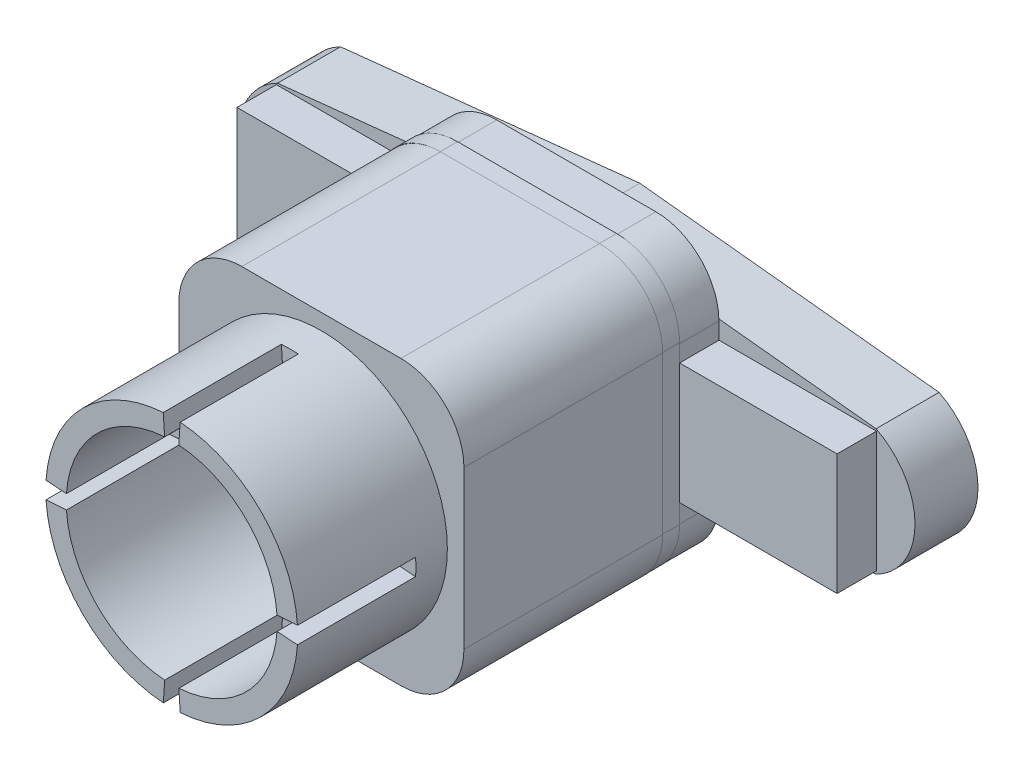
SolidWorks part; units mm, degrees
ref_plane "Front Plane" through (0, 0, 0) normal (0, 0, 1) x (1, 0, 0)
ref_plane "Top Plane" through (0, 0, 0) normal (0, 1, 0) x (1, 0, 0)
ref_plane "Right Plane" through (0, 0, 0) normal (1, 0, 0) x (0, 0, -1)
sketch "Sketch1" plane through (0, 0, 0) normal (0, 0, 1) x (1, 0, 0)
  line L12 (-5.05, 9.0001) -> (5.05, 9.0001)
  line L13 (-9.05, 5.0001) -> (-9.05, -5.0001)
  line L14 (-5.05, -9.0001) -> (5.05, -9.0001)
  line L15 (9.05, 5.0001) -> (9.05, -5.0001)
  line L16 (-9.05, 9.0001) -> (9.05, -9.0001) construction
  line L17 (-9.05, -9.0001) -> (9.05, 9.0001) construction
  arc A4 (-9.05, -5.0001) -> (-5.05, -9.0001) centre (-5.05, -5.0001) ccw
  arc A5 (5.05, -9.0001) -> (9.05, -5.0001) centre (5.05, -5.0001) ccw
  arc A6 (5.05, 9.0001) -> (9.05, 5.0001) centre (5.05, 5.0001) cw
  arc A7 (-5.05, 9.0001) -> (-9.05, 5.0001) centre (-5.05, 5.0001) ccw
  point P0 (0, 0)
  dimension "D2" = 4
  dimension "D1" = 9.05
extrude "Boss-Extrude1" add sketch "Sketch1" along normal blind 2
sketch "Sketch2" plane through (0, 0, 0) normal (0, 0, 1) x (1, 0, 0)
  line L0 (-5.05, 9.0001) -> (5.05, 9.0001)
  line L1 (-9.05, 5.0001) -> (-9.05, -5.0001)
  line L2 (-5.05, -9.0001) -> (5.05, -9.0001)
  line L3 (9.05, 5.0001) -> (9.05, -5.0001)
  line L4 (-9.05, 9.0001) -> (9.05, -9.0001) construction
  line L5 (-9.05, -9.0001) -> (9.05, 9.0001) construction
  arc A0 (-9.05, -5.0001) -> (-5.05, -9.0001) centre (-5.05, -5.0001) ccw
  arc A1 (5.05, -9.0001) -> (9.05, -5.0001) centre (5.05, -5.0001) ccw
  arc A2 (5.05, 9.0001) -> (9.05, 5.0001) centre (5.05, 5.0001) cw
  arc A3 (-5.05, 9.0001) -> (-9.05, 5.0001) centre (-5.05, 5.0001) ccw
  point P0 (0, 0)
  dimension "D2" = 4
  dimension "D1" = 9.05
extrude "Boss-Extrude2" add sketch "Sketch2" along normal blind 11.02
sketch "Sketch3" plane through (0, 0, 11.02) normal (0, 0, 1) x (1, 0, 0)
  line L1 (-5.05, 9.0001) -> (5.05, 9.0001)
  line L2 (-9.05, 5.0001) -> (-9.05, -5.0001)
  line L3 (-5.05, -9.0001) -> (5.05, -9.0001)
  line L4 (9.05, 5.0001) -> (9.05, -5.0001)
  line L5 (-9.05, 9.0001) -> (9.05, -9.0001) construction
  line L6 (-9.05, -9.0001) -> (9.05, 9.0001) construction
  arc A0 (-9.05, -5.0001) -> (-5.05, -9.0001) centre (-5.05, -5.0001) ccw
  arc A1 (5.05, -9.0001) -> (9.05, -5.0001) centre (5.05, -5.0001) ccw
  arc A2 (5.05, 9.0001) -> (9.05, 5.0001) centre (5.05, 5.0001) cw
  arc A3 (-5.05, 9.0001) -> (-9.05, 5.0001) centre (-5.05, 5.0001) ccw
  point P0 (0, 0)
  dimension "D2" = 4
  dimension "D1" = 9.05
extrude "Boss-Extrude3" add sketch "Sketch3" along normal blind 1.6
sketch "Sketch4" plane through (0, 0, 12.62) normal (0, 0, 1) x (1, 0, 0)
  circle A1 centre (0, 0) radius 8
  dimension "D2" = 16
extrude "Boss-Extrude4" add sketch "Sketch4" along normal blind 9.5
sketch "Sketch5" plane through (0, 0, 12.62) normal (0, 0, 1) x (1, 0, 0)
  circle A0 centre (0, 0) radius 6.65
  dimension "D1" = 13.3
extrude "Cut-Extrude1" cut sketch "Sketch5" along normal blind 20
sketch "Sketch12" plane through (0, 0, 0) normal (0, 0, -1) x (-1, 0, 0)
  line L0 (-5.0274, 8.9973) -> (5.0726, 8.9973)
  line L1 (-9.0274, 4.9973) -> (-9.0274, -5.0029)
  line L2 (-5.0274, -9.0029) -> (5.0726, -9.0029)
  line L3 (9.0726, 4.9973) -> (9.0726, -5.0029)
  line L4 (-9.0274, 8.9973) -> (9.0726, -9.0029) construction
  line L5 (-9.0274, -9.0029) -> (9.0726, 8.9973) construction
  arc A0 (-9.0274, -5.0029) -> (-5.0274, -9.0029) centre (-5.0274, -5.0029) ccw
  arc A1 (5.0726, -9.0029) -> (9.0726, -5.0029) centre (5.0726, -5.0029) ccw
  arc A2 (5.0726, 8.9973) -> (9.0726, 4.9973) centre (5.0726, 4.9973) cw
  arc A3 (-5.0274, 8.9973) -> (-9.0274, 4.9973) centre (-5.0274, 4.9973) ccw
  point P0 (0.0226, -0.0028)
  dimension "D2" = 4
  dimension "D1" = 9.05
extrude "Boss-Extrude5" add sketch "Sketch12" along normal blind 1.095 contours L0 A2 L3 A1 L2 A0 L1 A3
sketch "Sketch13" plane through (0, 0, 0) normal (0, 0, 1) x (1, 0, 0)
  circle A0 centre (0, 0) radius 6.7
  dimension "D1" = 13.4
extrude "Cut-Extrude3" cut sketch "Sketch13" against normal mid plane 60
sketch "Sketch15" plane through (0, 0, 22.12) normal (0, 0, 1) x (1, 0, 0)
  line L1 (-0.5528, 8.1871) -> (-0.0028, 0.0033)
  line L3 (0.5472, 8.1871) -> (-0.0028, 0.0033)
  line L4 (-0.5528, 8.1871) -> (-0.626, 9.0001)
  line L5 (5.05, 9.0001) -> (-5.05, 9.0001) construction
  line L6 (-0.626, 9.0001) -> (0.6172, 9.0001)
  line L7 (0.6172, 9.0001) -> (0.5472, 8.1871)
  dimension "D3" = 0.0732
  dimension "D4" = 0.07
extrude "Cut-Extrude4" cut sketch "Sketch15" against normal blind 7.5 contours L1 L3 L7 L6 L4
pattern_circular "CirPattern2" count 4 over 360 about axis through (0, 0, 0) along (0, 0, 1) of "Cut-Extrude4"
sketch "Sketch16" plane through (0, 0, -1.095) normal (0, 0, -1) x (-1, 0, 0)
  line L4 (-5.0236, 8.9395) -> (5.0767, 8.9395)
  line L6 (-5.0234, -8.9918) -> (5.0766, -8.9918)
  line L12 (-9.0234, 9.0084) -> (9.0766, -8.9918) construction
  line L13 (-9.0234, -8.9918) -> (9.0766, 9.0084) construction
  line L14 (0.0266, 0.0083) -> (0.0266, 11.7541) construction
  line L19 (-9.0274, 3.8808) -> (-19.0274, 3.8808)
  line L20 (-9.0274, 4.9973) -> (-9.0274, -5.0029) construction
  line L27 (-19.0274, 3.8808) -> (-19.0274, -3.7965)
  line L28 (-19.0274, -3.7965) -> (-9.0274, -3.7965)
  line L29 (-9.0274, 3.8808) -> (-9.0236, 4.9395)
  line L30 (-9.0274, -3.7965) -> (-9.0234, -4.9857)
  line L34 (9.0726, 3.8808) -> (19.0726, 3.8808)
  line L35 (9.0726, 4.9973) -> (9.0726, -5.0029) construction
  line L36 (19.0726, 3.8808) -> (19.0726, -4.5364)
  line L37 (19.0726, -4.5364) -> (9.0726, -4.5364)
  line L38 (9.0726, -4.5364) -> (9.0766, -4.9857)
  line L39 (9.0726, 3.8808) -> (9.0767, 4.9395)
  arc A6 (-9.0234, -4.9857) -> (-5.0234, -8.9918) centre (-5.0234, -4.9918) ccw
  arc A7 (5.0766, -8.9918) -> (9.0766, -4.9857) centre (5.0766, -4.9918) ccw
  arc A8 (5.0767, 8.9395) -> (9.0767, 4.9395) centre (5.0767, 4.9395) cw
  arc A9 (-5.0236, 8.9395) -> (-9.0236, 4.9395) centre (-5.0236, 4.9395) ccw
  point P0 (0.0266, 0.0083)
  point P17 (0.0266, 0.0083)
  point P22 (0, 0)
  point P23 (-13.5773, 0)
  point P32 (13.4528, 0.0083)
  point P34 (13.4528, 0.0083)
  point P43 (0, 0)
  dimension "D2" = 4
  dimension "D3" = 10
  dimension "D1" = 10
extrude "Boss-Extrude6" add sketch "Sketch16" along normal blind 2.5 separate body
sketch "Sketch17" plane through (0, 0, -3.595) normal (0, 0, -1) x (-1, 0, 0)
  line L0 (0, 6) -> (-19, 4)
  line L1 (-19, -4) -> (0, -6)
  line L2 (0, -6) -> (19, -4)
  line L3 (0, 6) -> (19, 4)
  line L4 (0, 3.7) -> (-16, 2.2)
  line L5 (-16, -2.2) -> (0, -3.7)
  line L6 (0, -3.7) -> (16, -2.1975)
  line L7 (0, 3.7) -> (16, 2.2)
  arc A1 (-19, 4) -> (-19, -4) centre (-17, 0) ccw
  arc A2 (19, 4) -> (19, -4) centre (17, 0) cw
  arc A3 (16, 2.2) -> (16, -2.1975) centre (15, 0.0013) cw
  arc A4 (-16, 2.2) -> (-16, -2.2) centre (-15, 0) ccw
  point P2 (0, 0)
  point P14 (0, 0)
  dimension "D2" = 2.2
  dimension "D3" = 2
  dimension "D4" = 2
  dimension "D6" = 16
  dimension "D7" = 1.5
  dimension "D8" = 1.5
  dimension "D9" = 19
  dimension "D10" = 19
  dimension "D11" = 2.2
  dimension "D12" = 4
  dimension "D13" = 4
  dimension "16" = 16
  dimension "D14" = 19
  dimension "D15" = 16
  dimension "D16" = 16
  dimension "D17" = 19
  dimension "D18" = 0
  dimension "D19" = 0
  dimension "D20" = 0
  dimension "D21" = 0
extrude "Boss-Extrude7" add sketch "Sketch17" along normal blind 4
